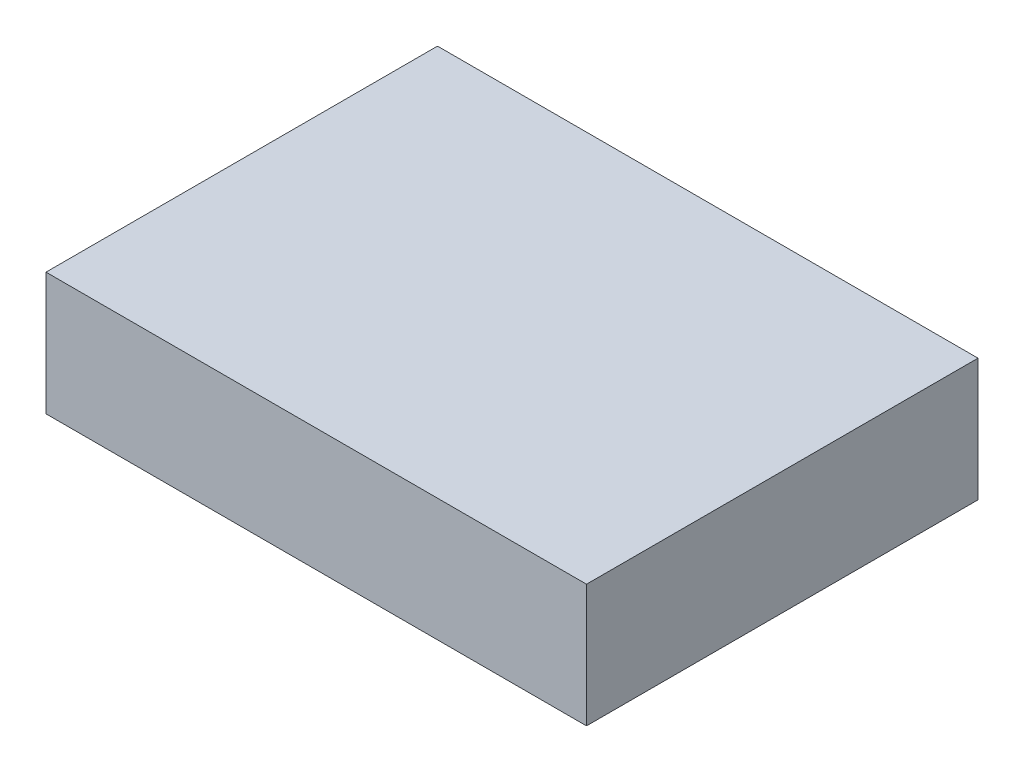
SolidWorks part; units mm, degrees
material "PBT General Purpose"
ref_plane "Front Plane" through (0, 0, 0) normal (0, 0, 1) x (1, 0, 0)
ref_plane "Top Plane" through (0, 0, 0) normal (0, 1, 0) x (1, 0, 0)
ref_plane "Right Plane" through (0, 0, 0) normal (1, 0, 0) x (0, 0, -1)
sketch "Sketch1" plane through (0, 0, 0) normal (0, 1, 0) x (1, 0, 0)
  line L1 (0, 0) -> (92.5, 0)
  line L2 (0, 0) -> (0, 67)
  line L3 (0, 67) -> (92.5, 67)
  line L4 (92.5, 0) -> (92.5, 67)
  line L5 (46.25, 67) -> (46.25, 0) construction
  line L6 (0, 33.5) -> (92.5, 33.5) construction
  point P72 (46.25, 33.5)
  dimension "D1" = 92.5
  dimension "D2" = 67
extrude "Boss-Extrude1" add sketch "Sketch1" along normal blind 21
